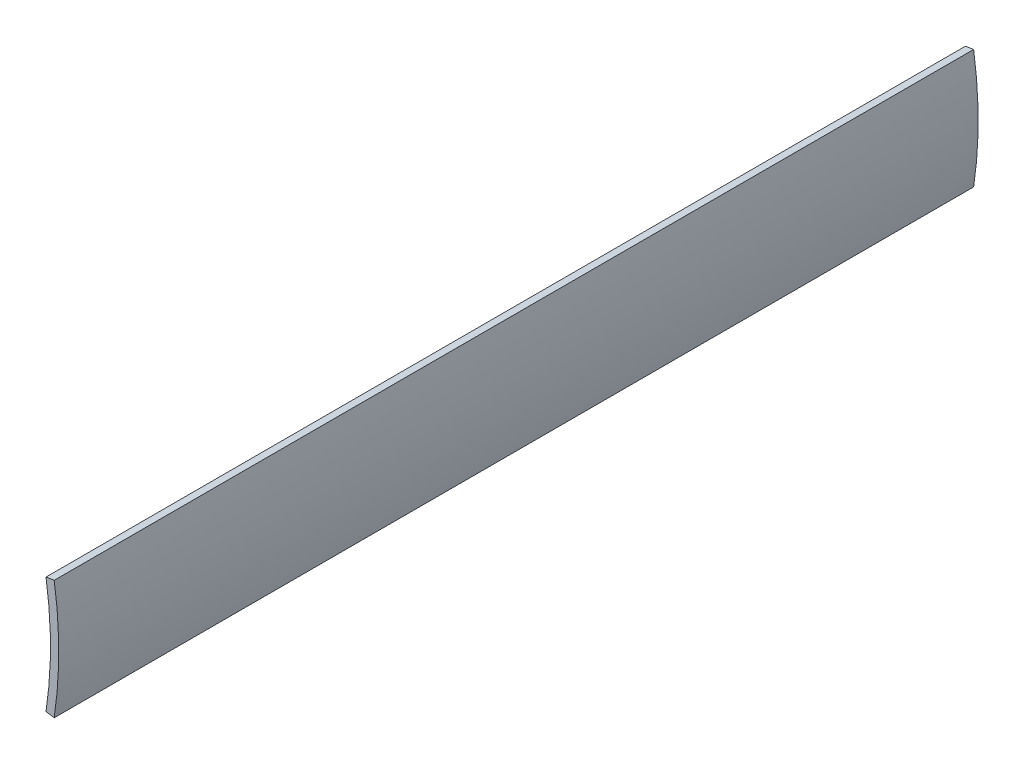
SolidWorks part; units mm, degrees
ref_plane "Front Plane" through (0, 0, 0) normal (0, 0, 1) x (1, 0, 0)
ref_plane "Top Plane" through (0, 0, 0) normal (0, 1, 0) x (1, 0, 0)
ref_plane "Right Plane" through (0, 0, 0) normal (1, 0, 0) x (0, 0, -1)
sketch "Sketch2" plane through (0, 0, 0) normal (0, 0, 1) x (1, 0, 0)
  line L0 (741.2711, 114.0925) -> (757.332, 116.5645)
  line L1 (741.2711, -114.0925) -> (757.332, -116.5645)
  arc A0 (741.2711, -114.0925) -> (741.2711, 114.0925) centre (0, 0) ccw
  arc A1 (757.332, -116.5645) -> (757.332, 116.5645) centre (0, 0) ccw
  point P6 (750, 0)
  point P7 (766.25, 0)
  dimension "D1" = 766.25
  dimension "D2" = 750
  dimension "D3" = 741.2711
extrude "Boss-Extrude1" add sketch "Sketch2" along normal blind 1800
